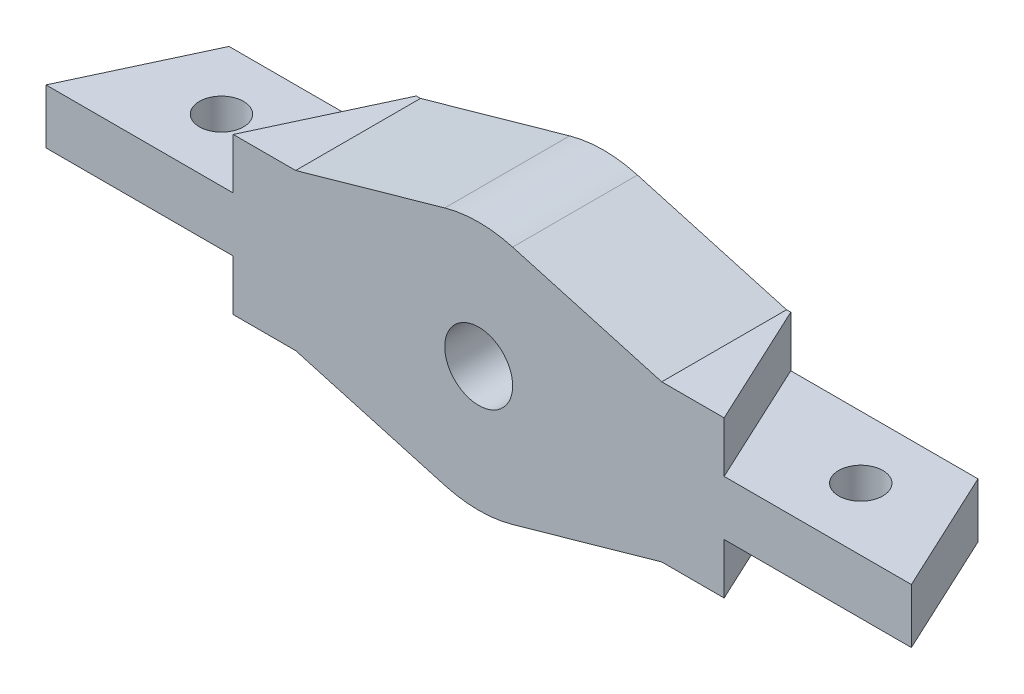
SolidWorks part; units mm, degrees
ref_plane "Front Plane" through (0, 0, 0) normal (0, 0, 1) x (1, 0, 0)
ref_plane "Top Plane" through (0, 0, 0) normal (0, 1, 0) x (1, 0, 0)
ref_plane "Right Plane" through (0, 0, 0) normal (1, 0, 0) x (0, 0, -1)
sketch "Sketch2" plane through (0, 0, 0) normal (0, 1, 0) x (1, 0, 0)
  line L0 (-19.05, 6.35) -> (19.05, 6.35)
  line L1 (19.05, 6.35) -> (24.9721, -6.35)
  line L2 (24.9721, -6.35) -> (-24.9721, -6.35)
  line L3 (-24.9721, -6.35) -> (-19.05, 6.35)
  line L4 (0, 6.35) -> (0, -6.35) construction
  point P6 (0, 0)
  dimension "D1" = 38.1
  dimension "D2" = 12.7
  dimension "D3" = 65
extrude "Boss-Extrude1" add sketch "Sketch2" along normal mid plane 25.4
sketch "Sketch5" plane through (0, 0, 6.35) normal (0, 0, 1) x (1, 0, 0)
  circle A0 centre (0, 0) radius 3.4544
  dimension "D1" = 6.9088
extrude "Cut-Extrude2" cut sketch "Sketch5" against normal through all
sketch "Sketch6" plane through (0, 0, 6.35) normal (0, 0, 1) x (1, 0, 0)
  line L0 (-24.9721, 12.7) -> (-24.9721, -12.7) construction
  line L1 (-24.9721, -2.7781) -> (-44.0221, -2.7781)
  line L2 (-24.9721, -2.7781) -> (-24.9721, 2.7781)
  line L3 (-24.9721, 2.7781) -> (-44.0221, 2.7781)
  line L4 (-44.0221, -2.7781) -> (-44.0221, 2.7781)
  line L5 (-24.9721, 12.7) -> (-24.9721, -12.7) construction
  point P10 (-24.9721, 0)
  point P11 (-24.9721, 0)
  dimension "D1" = 5.5562
  dimension "D2" = 19.05
sweep "Sweep1" add profiles "Sketch6" path edge at (-22.0111, 12.7, 0)
sketch "Sketch7" plane through (0, 0, 6.35) normal (0, 0, 1) x (1, 0, 0)
  line L0 (24.9721, 12.7) -> (24.9721, -12.7) construction
  line L1 (24.9721, -2.7781) -> (44.0221, -2.7781)
  line L2 (24.9721, -2.7781) -> (24.9721, 2.7781)
  line L3 (24.9721, 2.7781) -> (44.0221, 2.7781)
  line L4 (44.0221, -2.7781) -> (44.0221, 2.7781)
  line L5 (24.9721, -12.7) -> (24.9721, 12.7) construction
  point P8 (24.9721, 0)
  point P11 (24.9721, 0)
  dimension "D1" = 19.05
  dimension "D2" = 5.5562
sweep "Sweep2" add profiles "Sketch7" path edge at (22.0111, 12.7, 0)
sketch "Sketch8" plane through (0, 2.7781, 0) normal (0, 1, 0) x (1, 0, 0)
  line L0 (0, -6.985) -> (0, 6.985) construction
  line L1 (-19.05, 6.35) -> (-24.9721, -6.35) construction
  circle A0 centre (-32.5207, 0) radius 2.2479
  circle A1 centre (32.5207, 0) radius 2.2479
  dimension "D1" = 4.4958
  dimension "D2" = 9.525
extrude "Cut-Extrude3" cut sketch "Sketch8" against normal up to next
sketch "Sketch9" plane through (0, 0, 6.35) normal (0, 0, 1) x (1, 0, 0)
  line L0 (-24.9721, 12.7) -> (-24.9721, 2.7781) construction
  line L1 (-24.9721, 7.9375) -> (-18.6221, 7.9375)
  line L2 (-18.6221, 7.9375) -> (-3.4517, 12.2219)
  line L3 (-24.9721, 12.7) -> (24.9721, 12.7) construction
  line L4 (-24.9721, 7.9375) -> (-24.9721, 12.7)
  line L5 (-24.9721, 12.7) -> (0, 12.7)
  circle A0 centre (0, 0) radius 12.7
  line M8 (24.9721, 12.7) -> (-24.9721, 12.7)
  line M9 (-24.9721, 12.7) -> (-24.9721, 2.7781)
  dimension "D1" = 25.4
  dimension "D2" = 4.7625
  dimension "D3" = 6.35
extrude "Cut-Extrude4" cut sketch "Sketch9" against normal through all contours A0 L1 L2 M8 M9
mirror "Mirror1" about plane through (0, 0, 0) normal (1, 0, 0) of "Cut-Extrude4" second plane through (0, 0, 0) second plane normal (0, 1, 0)
